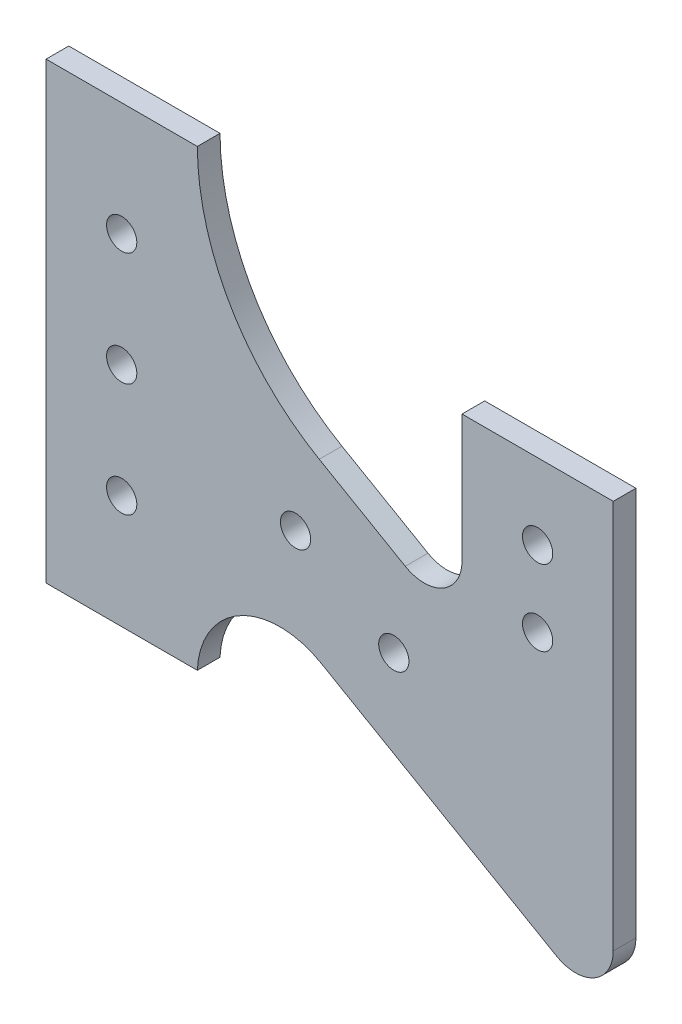
SolidWorks part; units mm, degrees
ref_plane "前视基准面" through (0, 0, 0) normal (0, 0, 1) x (1, 0, 0)
ref_plane "上视基准面" through (0, 0, 0) normal (0, 1, 0) x (1, 0, 0)
ref_plane "右视基准面" through (0, 0, 0) normal (1, 0, 0) x (0, 0, -1)
sketch "草图1" plane through (0, 0, 0) normal (0, 0, 1) x (1, 0, 0)
  line L0 (-8.2539, -13.1072) -> (22.8601, -31.0708)
  line L1 (30.3601, -26.7407) -> (30.3601, 24.7574)
  line L2 (30.3601, 24.7574) -> (10.3601, 24.7574)
  line L3 (10.3601, 24.7574) -> (10.3601, 7.9003)
  line L4 (2.8601, 3.5702) -> (-8.5147, 10.1374)
  line L5 (-24.6399, 37.9003) -> (-44.6399, 37.9003)
  line L6 (-44.6399, 37.9003) -> (-44.6399, -22.0997)
  line L7 (-44.6399, -22.0997) -> (-24.6399, -22.0997)
  circle A0 centre (-34.6399, 22.9003) radius 2
  circle A1 centre (-34.6399, 7.9003) radius 2
  circle A2 centre (-34.6399, -7.0997) radius 2
  circle A3 centre (-11.6495, 0.4003) radius 2
  arc A4 (22.8601, -31.0708) -> (30.3601, -26.7407) centre (25.3601, -26.7407) ccw
  arc A5 (2.8601, 3.5702) -> (10.3601, 7.9003) centre (5.3601, 7.9003) ccw
  arc A6 (-24.6399, 37.9003) -> (-8.5147, 10.1374) centre (7.6109, 38.0679) ccw
  arc A7 (-8.2539, -13.1072) -> (-24.6399, -22.0997) centre (-13.7193, -22.5736) ccw
  circle A8 centre (1.3408, -7.0997) radius 2
  circle A9 centre (20.3601, 4.7574) radius 2
  circle A10 centre (20.3601, 14.7574) radius 2
extrude "凸台-拉伸1" add sketch "草图1" along normal blind 3
